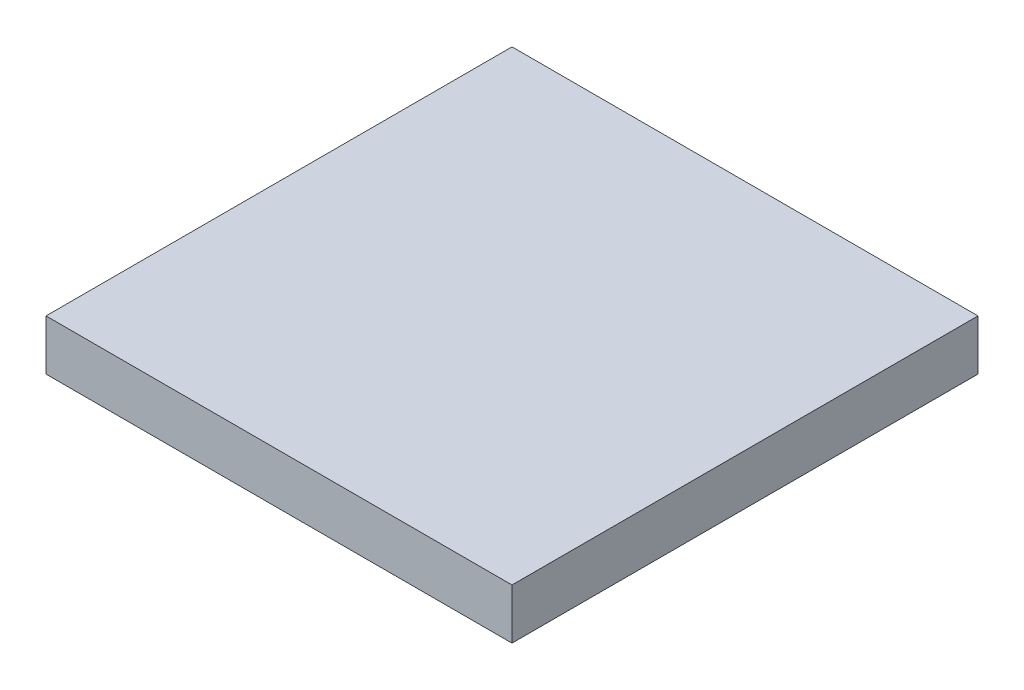
SolidWorks part; units mm, degrees
ref_plane "Front Plane" through (0, 0, 0) normal (0, 0, 1) x (1, 0, 0)
ref_plane "Top Plane" through (0, 0, 0) normal (0, 1, 0) x (1, 0, 0)
ref_plane "Right Plane" through (0, 0, 0) normal (1, 0, 0) x (0, 0, -1)
sketch "Sketch1" plane through (0, 0, 0) normal (0, 1, 0) x (1, 0, 0)
  line L1 (0, 0) -> (47.625, 0)
  line L2 (0, 0) -> (0, 47.625)
  line L3 (0, 47.625) -> (47.625, 47.625)
  line L4 (47.625, 0) -> (47.625, 47.625)
  dimension "D1" = 47.625
extrude "Boss-Extrude1" add sketch "Sketch1" along normal blind 5.15
equation "\"standard_thickness\"= 5.15mm"
equation "\"D1@Boss-Extrude1\"=\"standard_thickness\""
